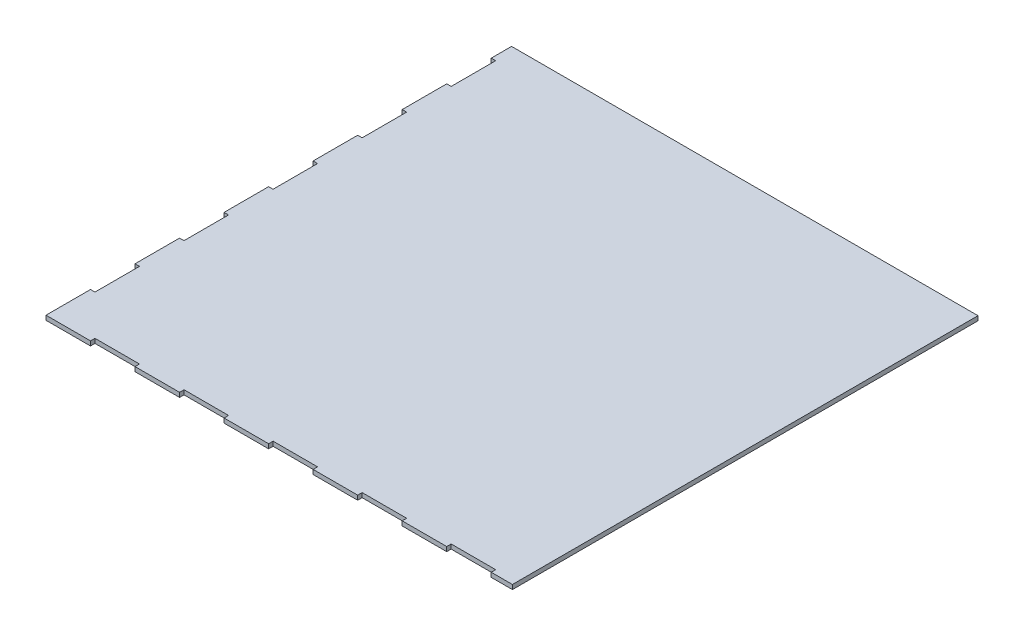
SolidWorks part; units mm, degrees
ref_plane "Front Plane" through (0, 0, 0) normal (0, 0, 1) x (1, 0, 0)
ref_plane "Top Plane" through (0, 0, 0) normal (0, 1, 0) x (1, 0, 0)
ref_plane "Right Plane" through (0, 0, 0) normal (1, 0, 0) x (0, 0, -1)
sketch "Sketch1" plane through (0, 0, 0) normal (0, 1, 0) x (1, 0, 0)
  line L1 (-315, -315) -> (315, -315)
  line L2 (-315, -315) -> (-315, 315)
  line L3 (-315, 315) -> (315, 315)
  line L4 (315, -315) -> (315, 315)
  line L5 (0, 315) -> (0, -315) construction
  line L6 (-315, 0) -> (315, 0) construction
  point P0 (0, 0)
extrude "Boss-Extrude1" add sketch "Sketch1" along normal blind 3
ref_plane "Plane1" through (0, 0, 285) normal (0, 0, 1) x (1, 0, 0)
sketch "Sketch3" plane through (0, 3, 0) normal (0, 1, 0) x (1, 0, 0)
  line L0 (-315, 315) -> (-315, -315) construction
  line L1 (-315, -285.0068) -> (-312, -285.0068)
  line L2 (-315, -285.0068) -> (-315, -255.0068)
  line L3 (-315, -255.0068) -> (-312, -255.0068)
  line L4 (-312, -285.0068) -> (-312, -255.0068)
  dimension "D1" = 30
  dimension "D2" = 3
extrude "Cut-Extrude2" cut sketch "Sketch3" against normal blind 3
pattern_linear "LPattern2" count 10 spacing 60 along (0, 0, -1) of "Cut-Extrude2"
ref_plane "Plane2" through (-0.725, 0, 0) normal (1, 0, 0) x (0, 0, -1)
mirror "Mirror1" about plane through (-0.725, 0, 0) normal (1, 0, 0) of "LPattern2", "Cut-Extrude2"
ref_plane "Plane3" through (-285, 0, 0) normal (-1, 0, 0) x (0, 0, 1)
sketch "Sketch5" plane through (0, 3, 0) normal (0, 1, 0) x (1, 0, 0)
  line L0 (-315, -315) -> (315, -315) construction
  line L1 (-285.0003, -315) -> (-255.0003, -315)
  line L2 (-285.0003, -315) -> (-285.0003, -312)
  line L3 (-285.0003, -312) -> (-255.0003, -312)
  line L4 (-255.0003, -315) -> (-255.0003, -312)
  dimension "D1" = 30
  dimension "D2" = 3
extrude "Cut-Extrude3" cut sketch "Sketch5" against normal blind 3
pattern_linear "LPattern3" count 10 spacing 60 along (1, 0, 0) of "Cut-Extrude3"
ref_plane "Plane4" through (0, 0, 1.295) normal (0, 0, 1) x (1, 0, 0)
mirror "Mirror2" about plane through (0, 0, 1.295) normal (0, 0, 1) of "LPattern3", "Cut-Extrude3"
other "SurfaceCut1"
other "SurfaceCut2"
